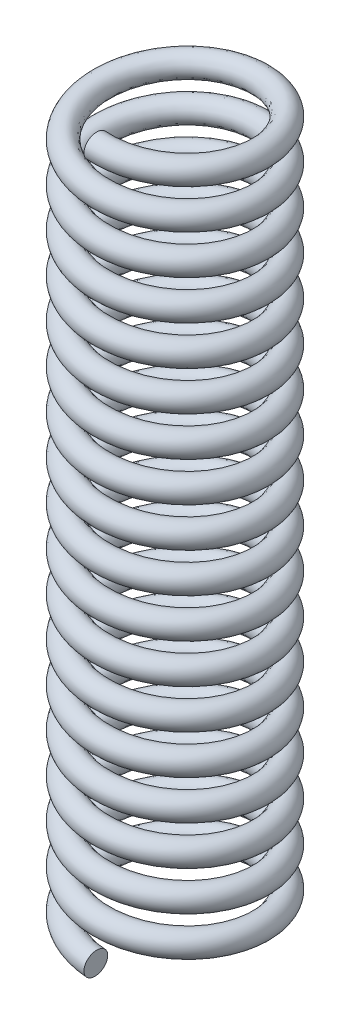
SolidWorks part; units mm, degrees
ref_plane "Front Plane" through (0, 0, 0) normal (0, 0, 1) x (1, 0, 0)
ref_plane "Top Plane" through (0, 0, 0) normal (0, 1, 0) x (1, 0, 0)
ref_plane "Right Plane" through (0, 0, 0) normal (1, 0, 0) x (0, 0, -1)
other "Configuration Table"
sketch "Sketch1" plane through (0, 0, 0) normal (0, 1, 0) x (1, 0, 0)
  circle A0 centre (0, 0) radius 4
curve "Coil_Helix" pitch 1.9889 height 35.8 turns 18
sweep "Coil_Wire" add path "Coil_Helix" circular profile diameter 1.2 parameters "D3"=1.2
